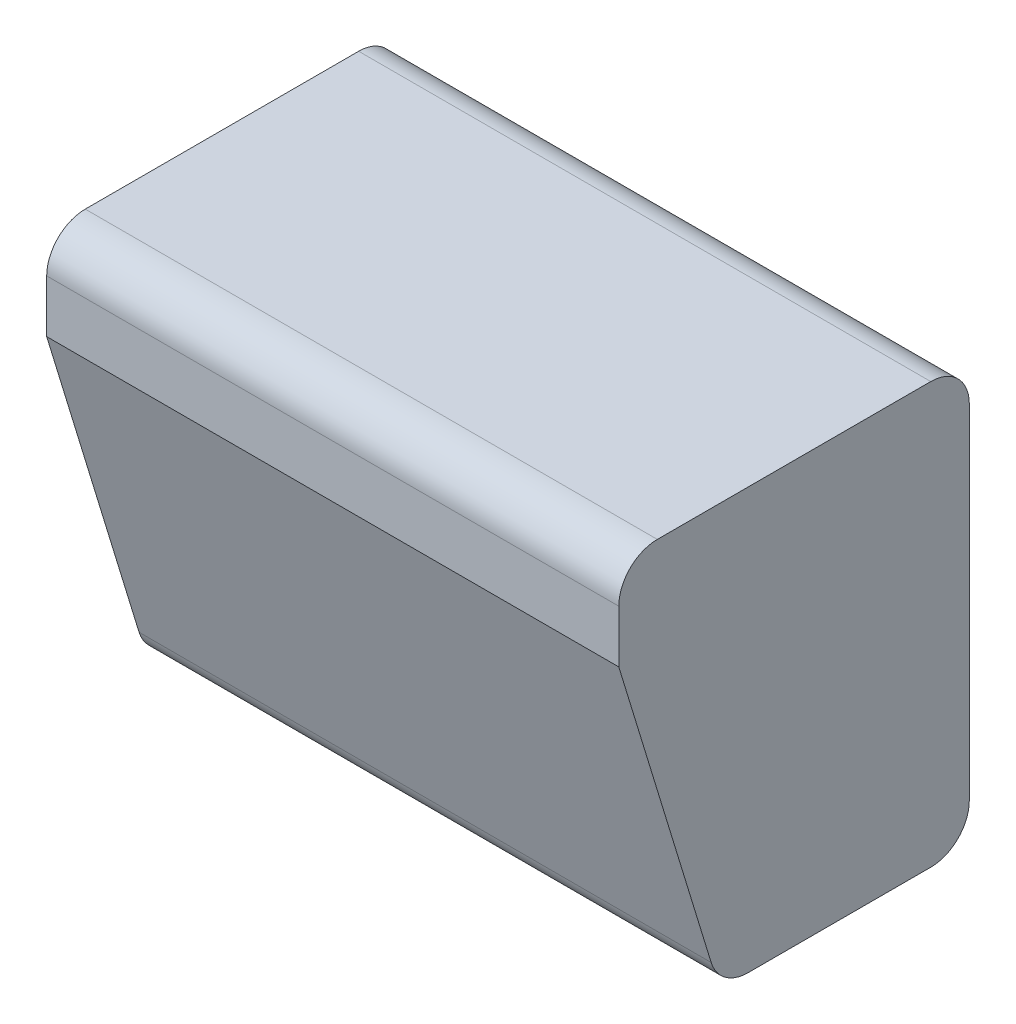
SolidWorks part; units mm, degrees
ref_plane "Front Plane" through (0, 0, 0) normal (0, 0, 1) x (1, 0, 0)
ref_plane "Top Plane" through (0, 0, 0) normal (0, 1, 0) x (1, 0, 0)
ref_plane "Right Plane" through (0, 0, 0) normal (1, 0, 0) x (0, 0, -1)
sketch "Sketch1" plane through (0, 0, 0) normal (1, 0, 0) x (0, 0, -1)
  line L0 (-27.3205, 28.1524) -> (22.6795, 28.1524)
  line L1 (22.6795, 28.1524) -> (22.6795, -31.8476)
  line L2 (22.6795, -31.8476) -> (-12.9511, -31.8476)
  line L3 (-12.9511, -31.8476) -> (-27.3205, 15.1524)
  line L4 (-27.3205, 15.1524) -> (-27.3205, 28.1524)
  dimension "D1" = 50
  dimension "D2" = 60
  dimension "D3" = 13
  dimension "D4" = 107
extrude "Boss-Extrude1" add sketch "Sketch1" along normal blind 81.6
fillet "Fillet1" radius 5.5 4 edges at (40.8, 28.1524, 27.3205) (40.8, -31.8476, 12.9511) (40.8, -31.8476, -22.6795) (40.8, 28.1524, -22.6795)
